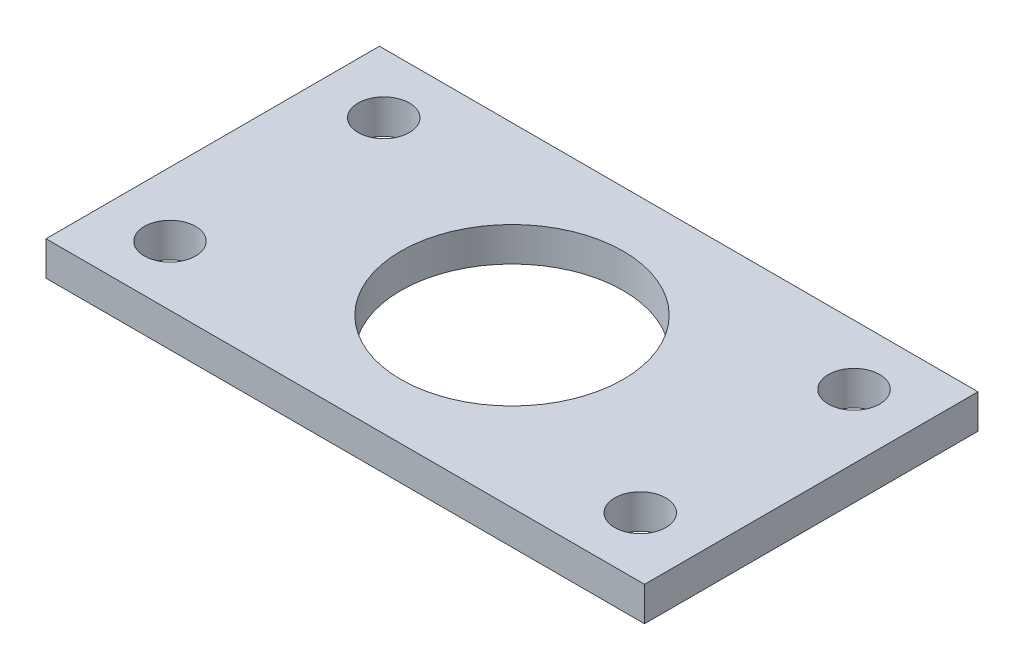
SolidWorks part; units mm, degrees
ref_plane "前视基准面" through (0, 0, 0) normal (0, 0, 1) x (1, 0, 0)
ref_plane "上视基准面" through (0, 0, 0) normal (0, 1, 0) x (1, 0, 0)
ref_plane "右视基准面" through (0, 0, 0) normal (1, 0, 0) x (0, 0, -1)
other "Configuration Table"
sketch "草图1" plane through (0, 0, 0) normal (0, 0, 1) x (1, 0, 0)
  line L0 (0, 0) -> (70, 0)
  line L1 (70, 0) -> (70, -4)
  line L2 (70, -4) -> (0, -4)
  line L3 (0, -4) -> (0, 0)
extrude "凸台-拉伸1" add sketch "草图1" along normal blind 39
sketch "草图2" plane through (0, 0, 0) normal (0, 1, 0) x (1, 0, 0)
  line L0 (0, 0) -> (0, -7)
  line L1 (0, -39) -> (0, 0) construction
  line L2 (0, -7) -> (7.5, -7)
  line L3 (0, -19.5) -> (70, -19.5)
  line L4 (70, 0) -> (0, 0) construction
  line L5 (70, -39) -> (70, 0) construction
  circle A0 centre (7.5, -7) radius 3
  circle A1 centre (62.5, -7) radius 3
  circle A2 centre (62.5, -32) radius 3
  circle A3 centre (7.5, -32) radius 3
  circle A4 centre (35, -19.5) radius 13
  dimension "D1" = 7.5
  dimension "D5" = 6
  dimension "D2" = 7
  dimension "D3" = 25
  dimension "D4" = 55
extrude "切除-拉伸1" cut sketch "草图2" against normal blind 5
